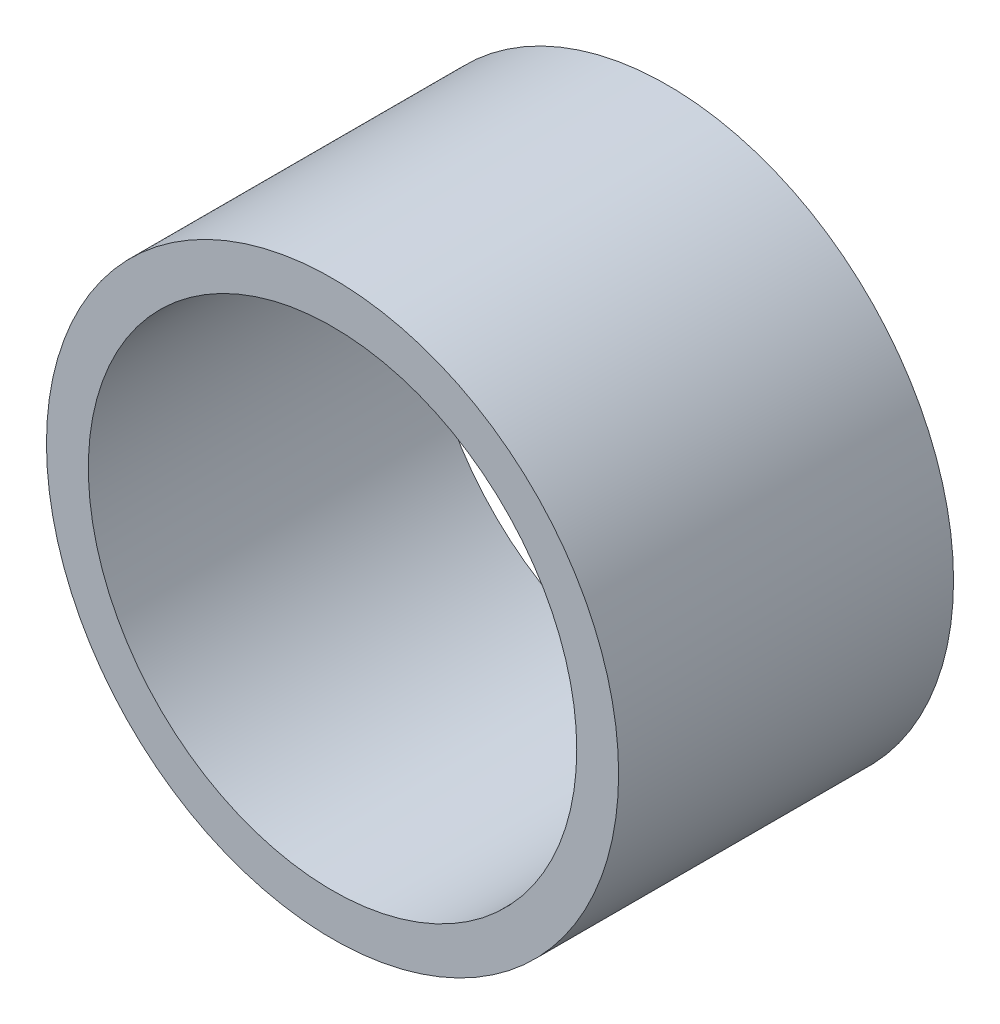
SolidWorks part; units mm, degrees
material "1.0050 (E295)"
ref_plane "Front Plane" through (0, 0, 0) normal (0, 0, 1) x (1, 0, 0)
ref_plane "Top Plane" through (0, 0, 0) normal (0, 1, 0) x (1, 0, 0)
ref_plane "Right Plane" through (0, 0, 0) normal (1, 0, 0) x (0, 0, -1)
sketch "Sketch1" plane through (0, 0, 0) normal (0, 0, 1) x (1, 0, 0)
  circle A0 centre (0, 0) radius 17.5
  circle A1 centre (0, 0) radius 20.5
  dimension "D1" = 35
  dimension "D2" = 41
extrude "Boss-Extrude1" add sketch "Sketch1" along normal blind 24
